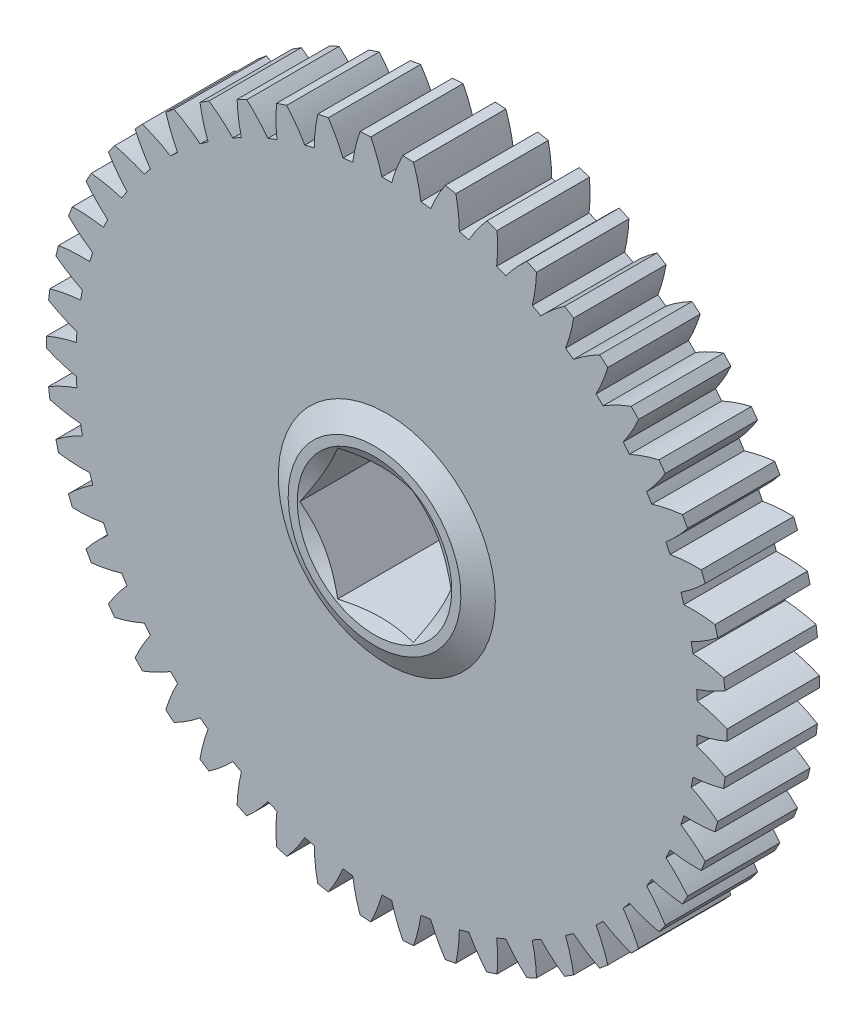
SolidWorks part; units mm, degrees
material "Alloy Steel"
ref_plane "Front Plane" through (0, 0, 0) normal (0, 0, 1) x (1, 0, 0)
ref_plane "Top Plane" through (0, 0, 0) normal (0, 1, 0) x (1, 0, 0)
ref_plane "Right Plane" through (0, 0, 0) normal (1, 0, 0) x (0, 0, -1)
sketch "Sketch1" plane through (0, 0, 0) normal (0, 0, 1) x (1, 0, 0)
  circle A0 centre (0, 0) radius 30.1625
  dimension "D1" = 60.325
extrude "Extrude1" add sketch "Sketch1" along normal mid plane 8.9662
sketch "Sketch2" plane through (0, 0, -4.4831) normal (0, 0, -1) x (-1, 0, 0)
  line L0 (33.02, 0.5187) -> (33.02, -0.5187)
  line L1 (33.02, 0) -> (30.1625, 0) construction
  arc A0 (33.02, 0.5187) -> (30.129, 1.4209) centre (27.06, -13.4968) ccw
  arc A1 (30.129, -1.4209) -> (33.02, -0.5187) centre (27.06, 13.4968) ccw
  circle A2 centre (0, 0) radius 30.1625 construction
  arc A3 (30.129, -1.4209) -> (30.129, 1.4209) centre (0, 0) ccw
  dimension "D4" = 15.2301
  dimension "D1" = 1.0374
  dimension "D2" = 2.8417
  dimension "D3" = 2.8575
extrude "Extrude2" add sketch "Sketch2" against normal up to surface (8.9662 mm away) up to face at (30.1625, 0, 4.4831)
pattern_circular "CirPattern1" count 50 over 360 about axis through (0, 0, 0) along (0, 0, 1) of "Extrude2"
ref_plane "Plane1" through (0, 0, 0) normal (1, 0, 0) x (0, 1, 0)
sketch "Sketch3" plane through (0, 0, 0) normal (1, 0, 0) x (0, 1, 0)
  line L0 (10.5304, 4.4831) -> (8.3819, 5.6769)
  line L1 (8.3819, 5.6769) -> (7.4931, 5.6769)
  line L2 (7.4931, 5.6769) -> (5.3446, 4.4831)
  line L3 (10.5304, 4.4831) -> (5.3446, 4.4831)
  line L4 (0, 8.9065) -> (0, 10.2197) construction
  line L5 (6.1166, 4.4831) -> (5.1858, 4.4831) construction
  dimension "D1" = 1.1938
  dimension "D2" = 10.6893
  dimension "D3" = 0.8888
  dimension "D4" = 5.1858
  dimension "D5" = 2.1485
revolve "Revolve1" add sketch "Sketch3" angle 360 about L4
sketch "Sketch4" plane through (0, 0, 0) normal (0, 0, 1) x (1, 0, 0)
  line L0 (-3.6662, -6.35) -> (3.6662, -6.35)
  line L1 (3.6662, -6.35) -> (7.3323, 0)
  line L2 (7.3323, 0) -> (3.6662, 6.35)
  line L3 (3.6662, 6.35) -> (-3.6662, 6.35)
  line L4 (-3.6662, 6.35) -> (-7.3323, 0)
  line L5 (-7.3323, 0) -> (-3.6662, -6.35)
  circle A0 centre (0, 0) radius 6.35 construction
  dimension "D1" = 12.7
extrude "Extrude3" cut sketch "Sketch4" against normal through all and the other way through all
